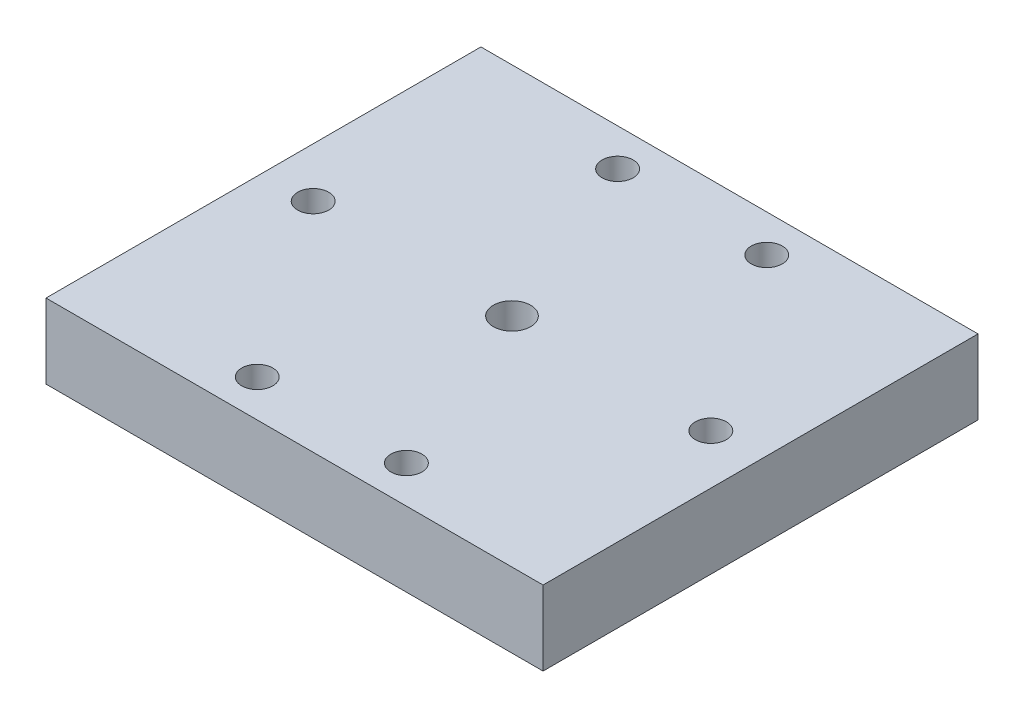
SolidWorks part; units mm, degrees
ref_plane "Front Plane" through (0, 0, 0) normal (0, 0, 1) x (1, 0, 0)
ref_plane "Top Plane" through (0, 0, 0) normal (0, 1, 0) x (1, 0, 0)
ref_plane "Right Plane" through (0, 0, 0) normal (1, 0, 0) x (0, 0, -1)
sketch "Sketch1" plane through (0, 0, 0) normal (0, 1, 0) x (1, 0, 0)
  line L0 (0, 11.644) -> (0, -12.635) construction
  line L1 (-20, 17.5) -> (20, 17.5)
  line L2 (-20, 17.5) -> (-20, -17.5)
  line L3 (-20, -17.5) -> (20, -17.5)
  line L4 (20, 17.5) -> (20, -17.5)
  line L5 (-20, 17.5) -> (20, -17.5) construction
  line L6 (-20, -17.5) -> (20, 17.5) construction
  line L7 (-4.1464, 0) -> (19.1602, 0) construction
  circle A0 centre (16, 0) radius 1.25
  circle A1 centre (6, -14.5) radius 1.25
  circle A2 centre (-6, -14.5) radius 1.25
  circle A3 centre (-16, 0) radius 1.25
  circle A4 centre (6, 14.5) radius 1.25
  circle A5 centre (-6, 14.5) radius 1.25
  circle A6 centre (0, 0) radius 1.5
  point P0 (0, 0)
  dimension "D2" = 2.5
  dimension "D7" = 3
  dimension "D1" = 12
  dimension "D3" = 29
  dimension "D4" = 35
  dimension "D5" = 40
  dimension "D6" = 32
extrude "Boss-Extrude1" add sketch "Sketch1" along normal blind 6
